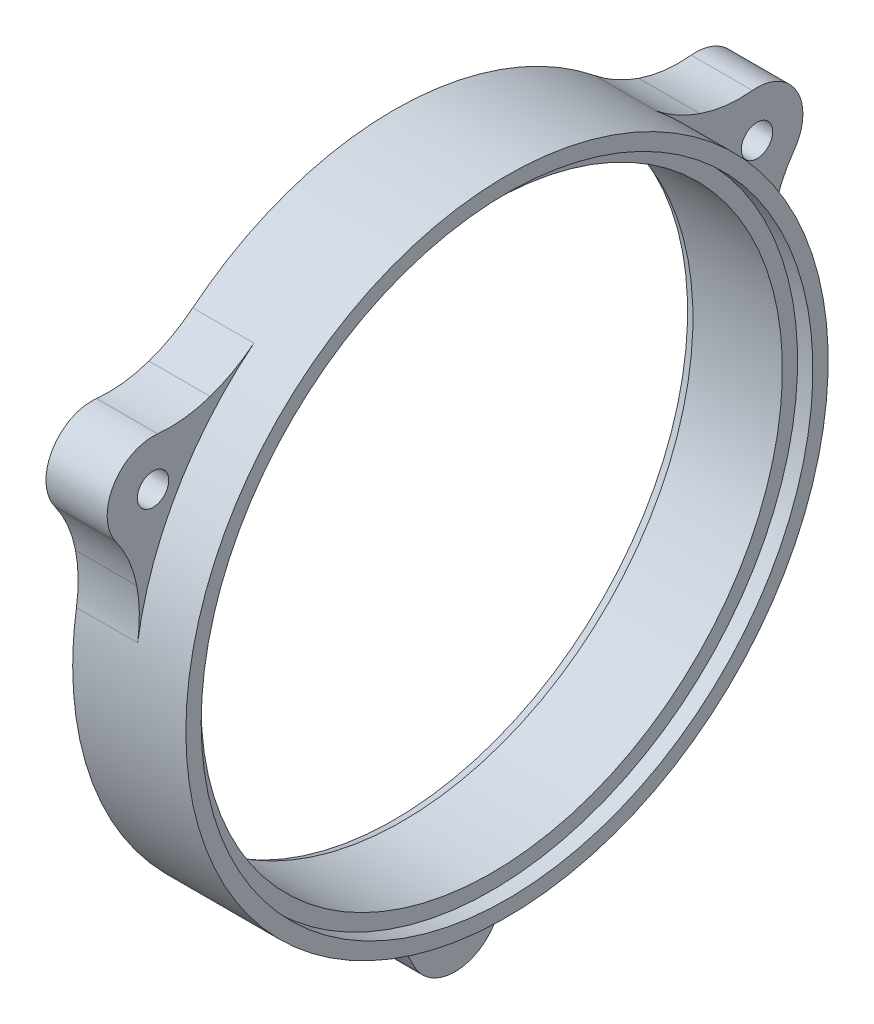
SolidWorks part; units mm, degrees
material "6061-T6 (SS)"
ref_plane "Front Plane" through (0, 0, 0) normal (0, 0, 1) x (1, 0, 0)
ref_plane "Top Plane" through (0, 0, 0) normal (0, 1, 0) x (1, 0, 0)
ref_plane "Right Plane" through (0, 0, 0) normal (1, 0, 0) x (0, 0, -1)
sketch "Sketch1" plane through (0, 0, 0) normal (0, 0, 1) x (1, 0, 0)
  line L0 (0, 0) -> (50000, 0) construction
  line L2 (0, 66.675) -> (23.495, 66.675)
  line L3 (23.495, 66.675) -> (23.495, 63.5)
  line L4 (23.495, 63.5) -> (20.32, 63.5)
  line L5 (20.32, 63.5) -> (20.32, 60.3504)
  line L6 (20.32, 60.3504) -> (0, 60.3504)
  line L7 (0, 60.3504) -> (0, 66.675)
  dimension "D1" = 20.32
  dimension "D2" = 133.35
  dimension "D3" = 3.175
  dimension "D4" = 120.7008
  dimension "D5" = 3.175
revolve "Revolve1" add sketch "Sketch1" angle 360 about L0
sketch "Sketch5" plane through (0, 0, 0) normal (-1, 0, 0) x (0, 0, 1)
  line L0 (8.5292, -4.9243) -> (-26667.7241, 15396.6177) construction
  line L1 (0, 0) -> (0, 50000) construction
  arc A0 (-61.7336, 45.6717) -> (-70.4197, 30.6271) centre (-62.6916, 36.195) ccw
  arc A2 (-66.0808, 20.5541) -> (-65.8943, 10.1735) centre (-96.0174, 14.8242) cw
  circle A3 centre (0, 0) radius 66.675 construction
  arc A4 (-50.8408, 46.9506) -> (-41.7576, 51.9794) centre (-60.8468, 75.7414) ccw
  arc A5 (-66.0808, 20.5541) -> (-70.4197, 30.6271) centre (-91.028, 15.7792) ccw
  arc A6 (-50.8408, 46.9506) -> (-61.7336, 45.6717) centre (-59.1791, 70.9429) cw
  arc A7 (-65.8943, 10.1735) -> (-41.7576, 51.9794) centre (0, 0) cw
  point P14 (-33.7808, 36.195)
  dimension "D1" = 30.48
  dimension "D2" = 25.4
  dimension "D3" = 9.525
  dimension "D4" = 72.39
  dimension "D5" = 30.48
  dimension "D6" = 60
extrude "Boss-Extrude1" add sketch "Sketch5" against normal blind 12.7
hole_wizard "1/4 Clearance Hole1" positions "Sketch7" profile "Sketch6" hole size "1/4" standard "Ansi Inch" end condition through all
sketch "Sketch7" plane through (0, 0, 0) normal (-1, 0, 0) x (0, 0, 1)
  arc A0 (-61.7336, 45.6717) -> (-70.4197, 30.6271) centre (-62.6916, 36.195) ccw construction
  point P0 (-62.6916, 36.195)
sketch "Sketch6" plane through (0, 36.195, -62.6916) normal (0, 1, 0) x (0, 0, 1)
  line L0 (0, 0) -> (0, 23.495)
  line L1 (0, 23.495) -> (3.2639, 23.495)
  line L2 (3.2639, 23.495) -> (3.2639, 0)
  line L5 (3.2639, 0) -> (0, 0)
  line L11 (0, -6.35) -> (0, 107.95) construction
  dimension "Thru Hole Dia." = 6.5278
  dimension "Thru Hole Depth" = 23.495
pattern_circular "CirPattern1" count 3 over 360 about axis through (0, 0, 0) along (1, 0, 0) of "Boss-Extrude1", "1/4 Clearance Hole1"
chamfer "Chamfer1" distance 0.635 angle 70 1 edges at (0, 0, 60.3504)
